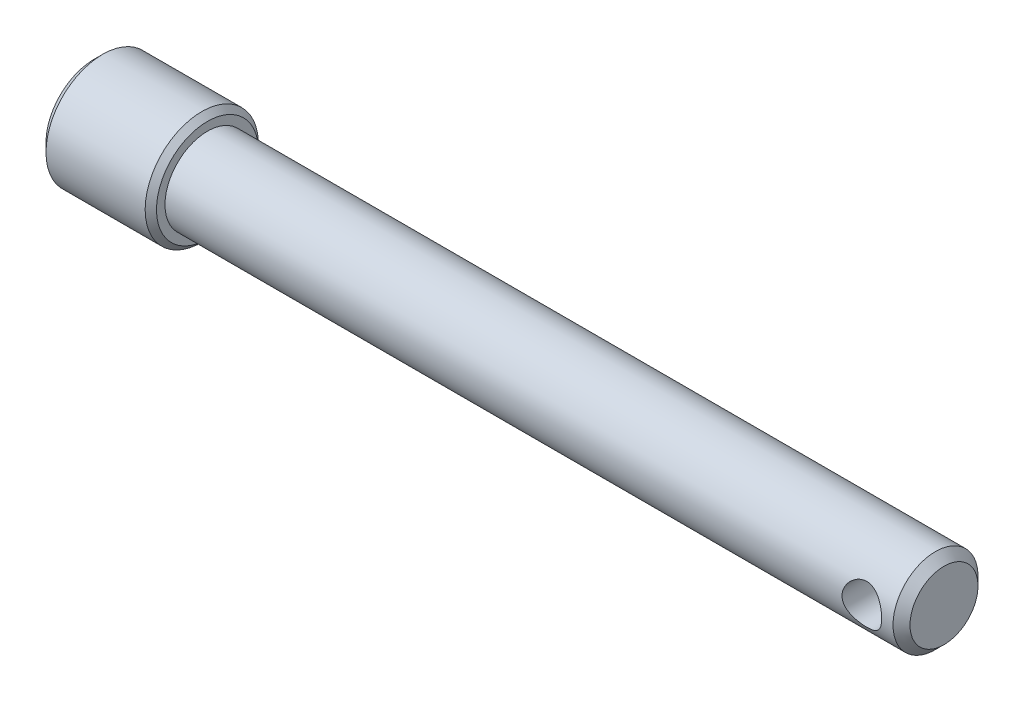
SolidWorks part; units mm, degrees
ref_plane "Plan de face" through (0, 0, 0) normal (0, 0, 1) x (1, 0, 0)
ref_plane "Plan de dessus" through (0, 0, 0) normal (0, 1, 0) x (1, 0, 0)
ref_plane "Plan de droite" through (0, 0, 0) normal (1, 0, 0) x (0, 0, -1)
sketch "Esquisse1" plane through (0, 0, 0) normal (0, 0, 1) x (1, 0, 0)
  line L0 (0, 0) -> (144.9502, 0) construction
  line L1 (0, 0) -> (0, 20)
  line L2 (0, 20) -> (40, 20)
  line L3 (40, 20) -> (40, 15)
  line L4 (40, 15) -> (300, 15)
  line L5 (300, 15) -> (300, 0)
  line L6 (0, 0) -> (300, 0)
  dimension "D1" = 40
  dimension "D2" = 30
  dimension "D3" = 40
  dimension "D4" = 300
revolve "Révolution1" add sketch "Esquisse1" angle 360 about L0
chamfer "Chanfrein1" distance 3 angle 45 1 edges at (0, 0, 20)
chamfer "Chanfrein2" distance 3 angle 45 1 edges at (300, 0, 15)
sketch "Esquisse2" plane through (0, 0, 0) normal (0, 0, 1) x (1, 0, 0)
  line L0 (300, -12) -> (300, 12) construction
  line L1 (0, 0) -> (200.3732, 0) construction
  circle A0 centre (286, 0) radius 7
  dimension "D1" = 14
  dimension "D2" = 14
extrude "Enlèv. mat.-Extru.1" cut sketch "Esquisse2" against normal mid plane 90
chamfer "Chanfrein3" distance 2 angle 45 1 edges at (40, 0, 20)
